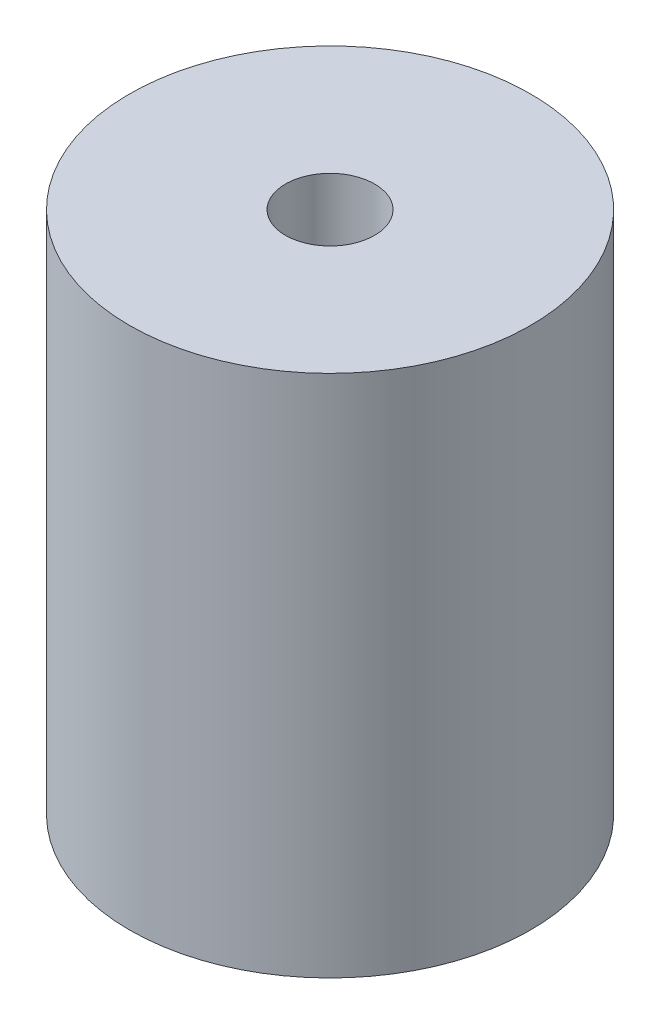
SolidWorks part; units mm, degrees
ref_plane "Front Plane" through (0, 0, 0) normal (0, 0, 1) x (1, 0, 0)
ref_plane "Top Plane" through (0, 0, 0) normal (0, 1, 0) x (1, 0, 0)
ref_plane "Right Plane" through (0, 0, 0) normal (1, 0, 0) x (0, 0, -1)
sketch "Sketch1" plane through (0, 0, 0) normal (0, 1, 0) x (1, 0, 0)
  circle A0 centre (0, 0) radius 4
  circle A1 centre (0, 0) radius 18
extrude "Boss-Extrude1" add sketch "Sketch1" against normal blind 47
